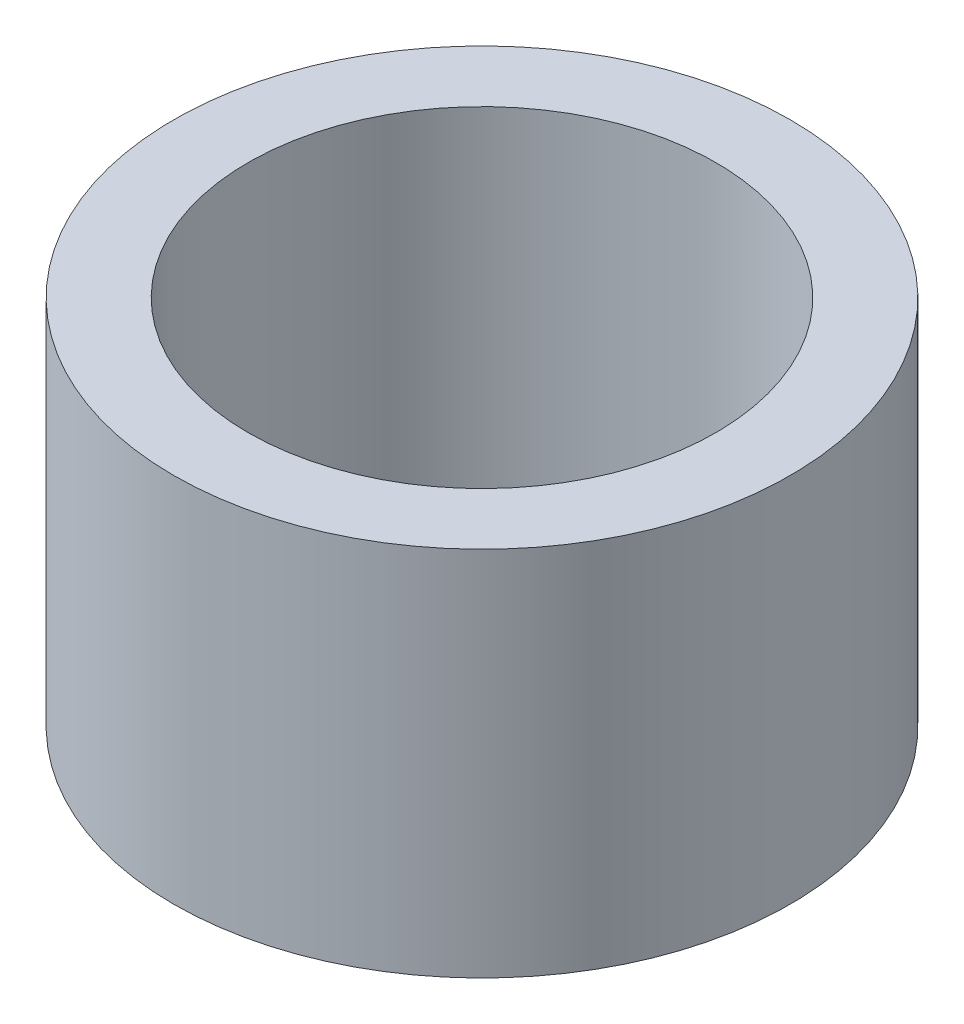
SolidWorks part; units mm, degrees
ref_plane "Front Plane" through (0, 0, 0) normal (0, 0, 1) x (1, 0, 0)
ref_plane "Top Plane" through (0, 0, 0) normal (0, 1, 0) x (1, 0, 0)
ref_plane "Right Plane" through (0, 0, 0) normal (1, 0, 0) x (0, 0, -1)
sketch "Sketch1" plane through (0, 0, 0) normal (0, 1, 0) x (1, 0, 0)
  circle A0 centre (0, 0) radius 4
  circle A1 centre (0, 0) radius 5.27
  dimension "D1" = 8
  dimension "D2" = 1.27
extrude "Boss-Extrude1" add sketch "Sketch1" along normal blind 6.35
